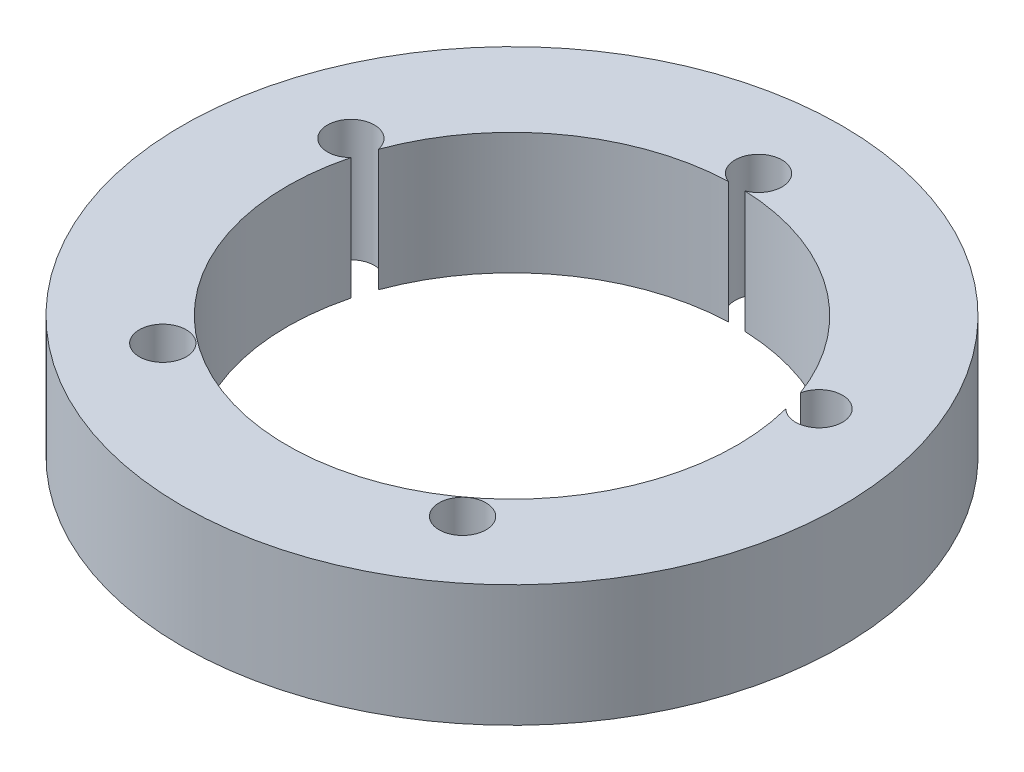
SolidWorks part; units mm, degrees
ref_plane "前基準面" through (0, 0, 0) normal (0, 0, 1) x (1, 0, 0)
ref_plane "上基準面" through (0, 0, 0) normal (0, 1, 0) x (1, 0, 0)
ref_plane "右基準面" through (0, 0, 0) normal (1, 0, 0) x (0, 0, -1)
sketch "草圖1" plane through (0, 0, 0) normal (0, 1, 0) x (1, 0, 0)
  circle A0 centre (0, 0) radius 24
  dimension "D1" = 48
extrude "伸長-薄件1" add sketch "草圖1" along normal blind 13 thin
sketch "草圖2" plane through (0, 0, 0) normal (0, 1, 0) x (1, 0, 0)
  line L0 (0, -978.5) -> (0, 49021.5) construction
  line L1 (-1000, 26.3308) -> (49000, 26.3308) construction
  circle A1 centre (0, 26.3308) radius 2.505
  dimension "D1" = 5.01
extrude "除料-伸長1" cut sketch "草圖2" along normal blind 16
sketch "草圖11" plane through (0, 13, 0) normal (0, 1, 0) x (1, 0, 0)
  line L0 (-13.5981, -21.1952) -> (13.4119, -21.1952) construction
  circle A0 centre (-16.1031, -21.1952) radius 2.505
  circle A1 centre (15.9169, -21.1952) radius 2.505
  dimension "D1" = 5.01
  dimension "D3" = 5.01
  dimension "D4" = 2.505
  dimension "D2" = 27.01
extrude "除料-伸長3" cut sketch "草圖11" against normal blind 16
sketch "草圖12" plane through (0, 13, 0) normal (0, 1, 0) x (1, 0, 0)
  line L0 (-1023, 12.4699) -> (48977, 12.4699) construction
  line L2 (-1021.546, 5.2895) -> (48978.454, 5.2895) construction
  line L3 (-1025, 7.7945) -> (48975, 7.7945) construction
  line L4 (0, -200978.5) -> (0, 249021.5) construction
  circle A2 centre (-25, 7.7945) radius 2.505
  circle A3 centre (25, 7.7945) radius 2.505
  dimension "D1" = 5.01
  dimension "D2" = 5.01
  dimension "D3" = 25
  dimension "D4" = 25
extrude "除料-伸長4" cut sketch "草圖12" against normal blind 16
